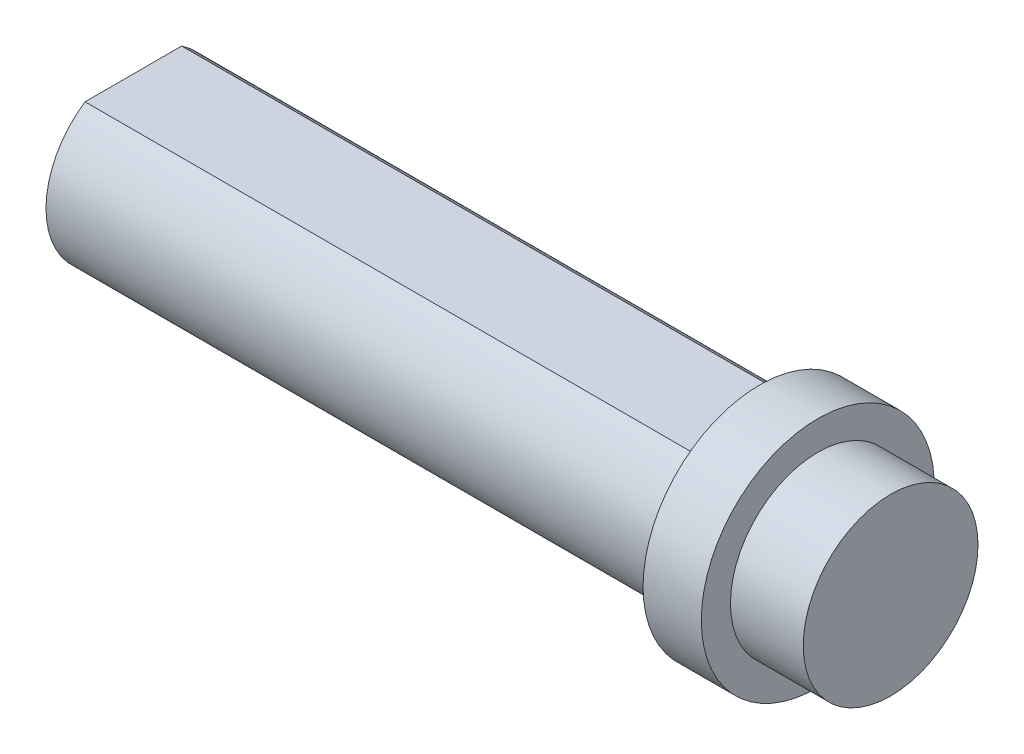
SolidWorks part; units mm, degrees
ref_plane "前视基准面" through (0, 0, 0) normal (0, 0, 1) x (1, 0, 0)
ref_plane "上视基准面" through (0, 0, 0) normal (0, 1, 0) x (1, 0, 0)
ref_plane "右视基准面" through (0, 0, 0) normal (1, 0, 0) x (0, 0, -1)
sketch "Sketch1" plane through (0, 0, 0) normal (1, 0, 0) x (0, 0, -1)
  circle A0 centre (0, 0) radius 3
extrude "Boss-Extrude1" add sketch "Sketch1" along normal blind 26
sketch "Sketch2" plane through (0, 0, 0) normal (-1, 0, 0) x (0, 0, 1)
  line L0 (-0.8359, 2.5) -> (1.1857, 2.5) construction
  line L1 (-1.6583, 2.5) -> (1.6583, 2.5)
  arc A0 (1.6583, 2.5) -> (-1.6583, 2.5) centre (0, 0) ccw
  dimension "D1" = 2.5
extrude "Cut-Extrude1" cut sketch "Sketch2" against normal blind 21.5
ref_plane "Plane1" through (21.5, 0, 0) normal (-1, 0, 0) x (0, 0, 1)
sketch "Sketch3" plane through (21.5, 0, 0) normal (-1, 0, 0) x (0, 0, 1)
  circle A0 centre (0, 0) radius 3
  circle A1 centre (0, 0) radius 4
  dimension "D1" = 8
extrude "Boss-Extrude2" add sketch "Sketch3" against normal blind 2
sketch "Sketch4" plane through (0, 0, 0) normal (0, 0, 1) x (1, 0, 0)
  line L0 (21, 2.5) -> (21.5, 2.75)
  line L1 (21.5, 2.5) -> (0, 2.5) construction
  line L2 (21.5, 4) -> (21.5, -4) construction
  line L3 (21.5, 2.75) -> (21.5, 2.5)
  line L4 (21.5, 2.5) -> (21, 2.5)
  dimension "D1" = 0.5
  dimension "D2" = 0.25
extrude "Boss-Extrude3" add sketch "Sketch4" along normal mid plane 3.32
